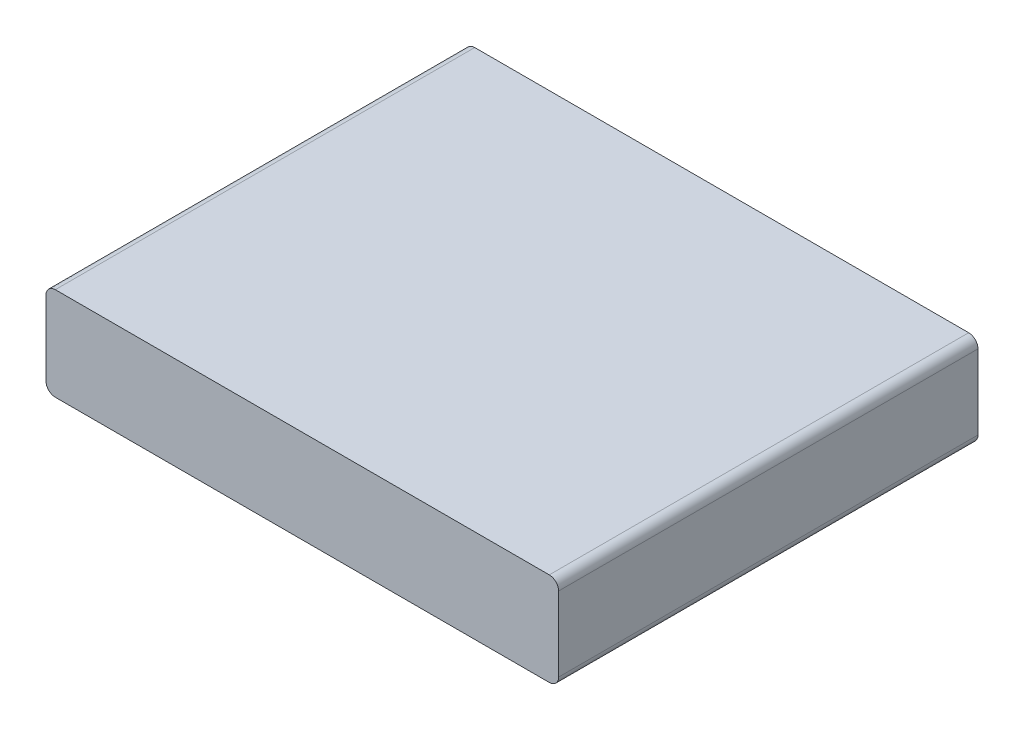
SolidWorks part; units mm, degrees
material "Oak"
ref_plane "Front Plane" through (0, 0, 0) normal (0, 0, 1) x (1, 0, 0)
ref_plane "Top Plane" through (0, 0, 0) normal (0, 1, 0) x (1, 0, 0)
ref_plane "Right Plane" through (0, 0, 0) normal (1, 0, 0) x (0, 0, -1)
sketch "Sketch2" plane through (0, 0, 0) normal (0, 1, 0) x (1, 0, 0)
  line L1 (-163.9124, 242.9732) -> (386.0876, 242.9732)
  line L2 (-163.9124, 242.9732) -> (-163.9124, -207.0268)
  line L3 (-163.9124, -207.0268) -> (386.0876, -207.0268)
  line L4 (386.0876, 242.9732) -> (386.0876, -207.0268)
  dimension "D1" = 550
  dimension "D2" = 450
extrude "Boss-Extrude1" add sketch "Sketch2" along normal blind 100
fillet "Fillet2" radius 10 4 edges at (386.0876, 0, -17.9732) (386.0876, 100, -17.9732) (-163.9124, 0, -17.9732) (-163.9124, 100, -17.9732)
